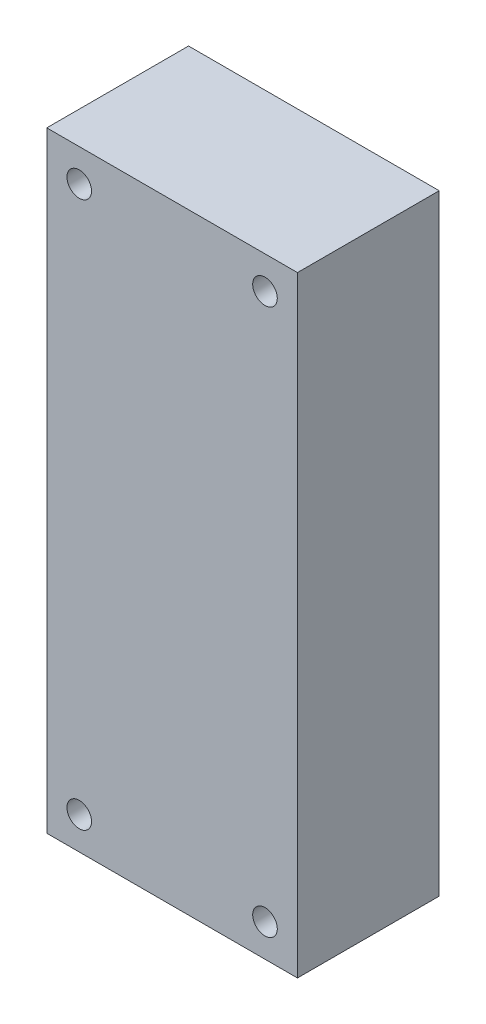
SolidWorks part; units mm, degrees
material "ABS"
ref_plane "前基準面" through (0, 0, 0) normal (0, 0, 1) x (1, 0, 0)
ref_plane "上基準面" through (0, 0, 0) normal (0, 1, 0) x (1, 0, 0)
ref_plane "右基準面" through (0, 0, 0) normal (1, 0, 0) x (0, 0, -1)
sketch "草圖1" plane through (0, 0, 0) normal (0, 0, 1) x (1, 0, 0)
  line L0 (0, 0) -> (0, 39.8045) construction
  line L1 (-12.74, 31.05) -> (12.74, 31.05)
  line L2 (-12.74, 31.05) -> (-12.74, -31.05)
  line L3 (-12.74, -31.05) -> (12.74, -31.05)
  line L4 (12.74, 31.05) -> (12.74, -31.05)
  line L5 (0, 0) -> (31.7622, 0) construction
  circle A0 centre (9.44, 27.75) radius 1.25
  circle A1 centre (-9.44, 27.75) radius 1.25
  circle A2 centre (9.44, -27.75) radius 1.25
  circle A3 centre (-9.44, -27.75) radius 1.25
  dimension "D3" = 2.5
  dimension "D1" = 62.1
  dimension "D2" = 25.48
  dimension "D4" = 3.3
  dimension "D5" = 3.3
extrude "填料-伸長1" add sketch "草圖1" along normal blind 14.41
